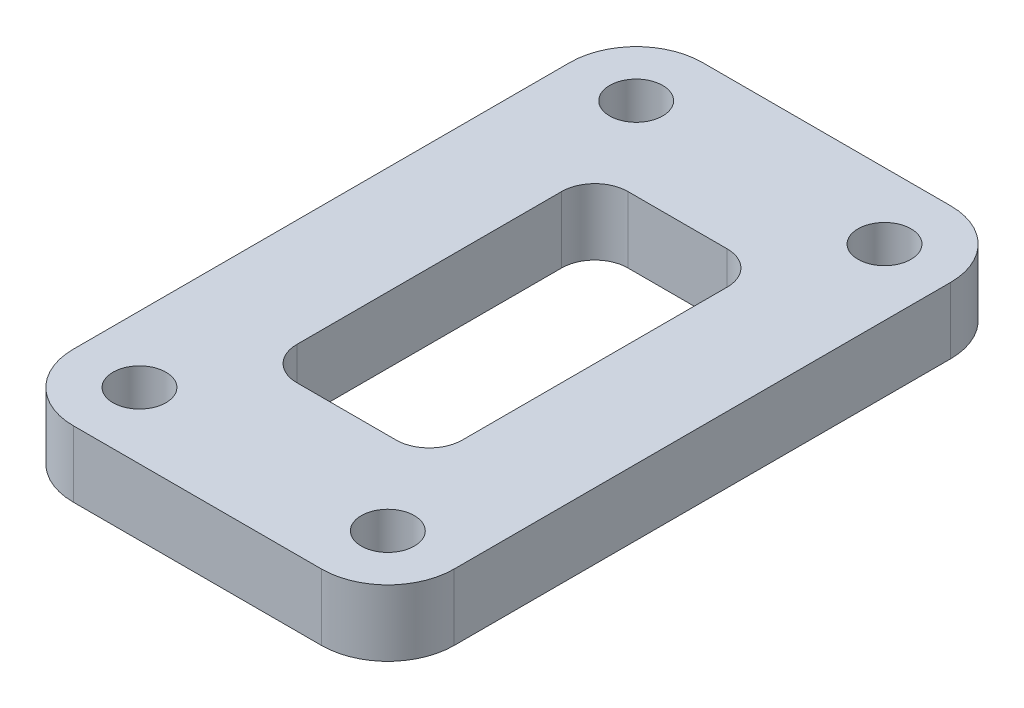
SolidWorks part; units mm, degrees
ref_plane "Front Plane" through (0, 0, 0) normal (0, 0, 1) x (1, 0, 0)
ref_plane "Top Plane" through (0, 0, 0) normal (0, 1, 0) x (1, 0, 0)
ref_plane "Right Plane" through (0, 0, 0) normal (1, 0, 0) x (0, 0, -1)
sketch "Sketch1" plane through (0, 0, 0) normal (0, 1, 0) x (1, 0, 0)
  line L0 (-11.5, 15) -> (-11.5, -15)
  line L1 (-7.5, 15) -> (7.5, 15) construction
  line L2 (-7.5, 15) -> (-7.5, -15) construction
  line L3 (-7.5, -15) -> (7.5, -15) construction
  line L4 (7.5, 15) -> (7.5, -15) construction
  line L5 (-7.5, -19) -> (7.5, -19)
  line L6 (11.5, 15) -> (11.5, -15)
  line L7 (-7.5, 19) -> (7.5, 19)
  line L8 (-11.5, 19) -> (-11.5, -19) construction
  line L9 (-11.5, -19) -> (11.5, -19) construction
  line L10 (11.5, 19) -> (11.5, -19) construction
  line L11 (-11.5, 19) -> (11.5, 19) construction
  circle A0 centre (-7.5, 15) radius 1.6
  circle A1 centre (7.5, 15) radius 1.6
  circle A2 centre (-7.5, -15) radius 1.6
  circle A3 centre (7.5, -15) radius 1.6
  arc A4 (-11.5, -15) -> (-7.5, -19) centre (-7.5, -15) ccw
  arc A5 (7.5, -19) -> (11.5, -15) centre (7.5, -15) ccw
  arc A6 (11.5, 15) -> (7.5, 19) centre (7.5, 15) ccw
  arc A7 (-11.5, 15) -> (-7.5, 19) centre (-7.5, 15) cw
  point P4 (0, 15)
  point P6 (-7.5, 0)
  dimension "D4" = 3.2
  dimension "D5" = 4
  dimension "D1" = 15
  dimension "D2" = 30
  dimension "D3" = 4
extrude "Boss-Extrude1" add sketch "Sketch1" along normal blind 4
sketch "Sketch2" plane through (0, 4, 0) normal (0, 1, 0) x (1, 0, 0)
  line L1 (-3, 10) -> (3, 10)
  line L2 (-5, 8) -> (-5, -8)
  line L3 (-3, -10) -> (3, -10)
  line L4 (5, 8) -> (5, -8)
  arc A0 (3, -10) -> (5, -8) centre (3, -8) ccw
  arc A1 (-5, -8) -> (-3, -10) centre (-3, -8) ccw
  arc A2 (3, 10) -> (5, 8) centre (3, 8) cw
  arc A3 (-3, 10) -> (-5, 8) centre (-3, 8) ccw
  point P4 (0, 10)
  point P6 (-5, 0)
  point P11 (-5, -10)
  point P14 (5, 10)
  point P17 (-5, 10)
  dimension "D3" = 2
  dimension "D1" = 10
  dimension "D2" = 20
extrude "Cut-Extrude1" cut sketch "Sketch2" against normal through all
